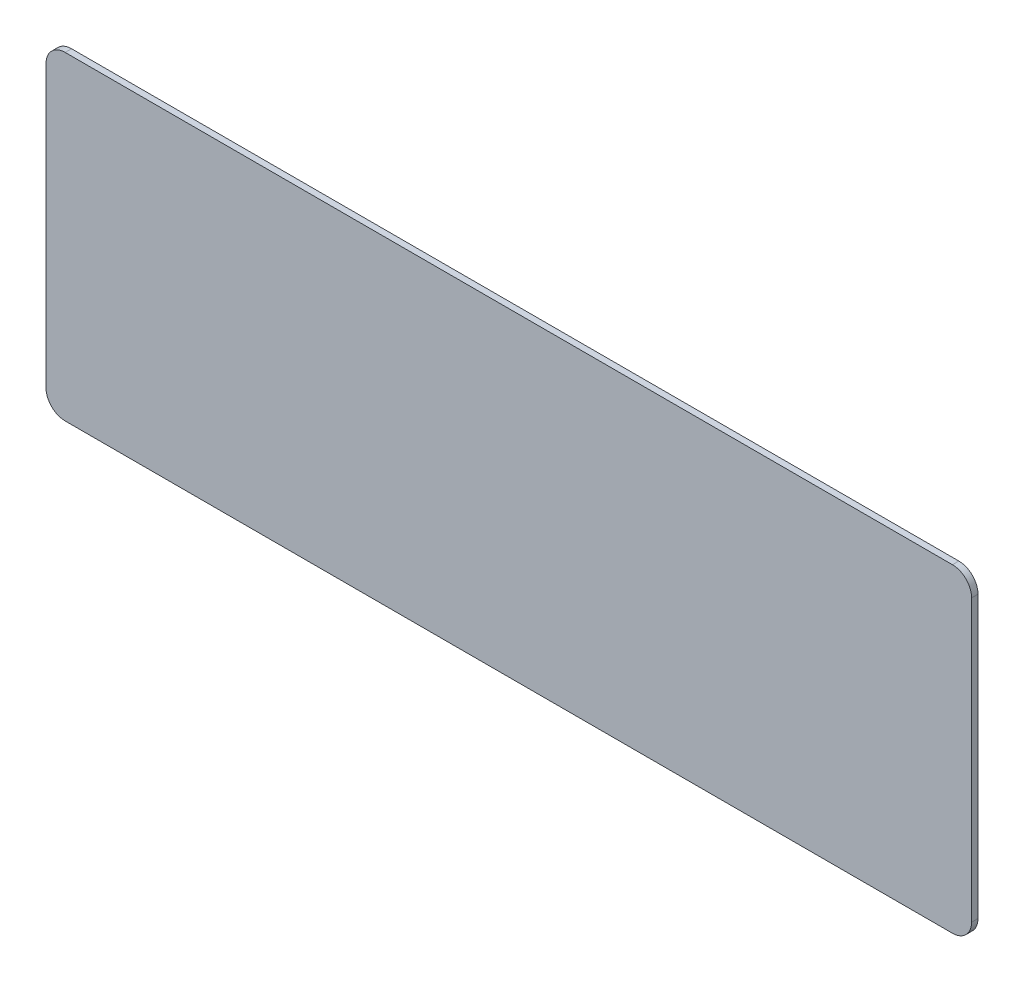
SolidWorks part; units mm, degrees
material "Thornel Mat VMA"
ref_plane "前视基准面" through (0, 0, 0) normal (0, 0, 1) x (1, 0, 0)
ref_plane "上视基准面" through (0, 0, 0) normal (0, 1, 0) x (1, 0, 0)
ref_plane "右视基准面" through (0, 0, 0) normal (1, 0, 0) x (0, 0, -1)
other "Configuration Table"
sketch "草图1" plane through (0, 0, 0) normal (0, 0, 1) x (1, 0, 0)
  line L1 (-72.5, 25) -> (72.5, 25)
  line L2 (-72.5, 25) -> (-72.5, -25)
  line L3 (-72.5, -25) -> (72.5, -25)
  line L4 (72.5, 25) -> (72.5, -25)
  line L5 (-72.5, 25) -> (72.5, -25) construction
  line L6 (-72.5, -25) -> (72.5, 25) construction
  point P0 (0, 0)
  dimension "D1" = 145
  dimension "D2" = 50
extrude "凸台-拉伸1" add sketch "草图1" along normal blind 1
fillet "圆角1" radius 3 4 edges at (-72.5, -25, 0.5) (72.5, -25, 0.5) (72.5, 25, 0.5) (-72.5, 25, 0.5)
